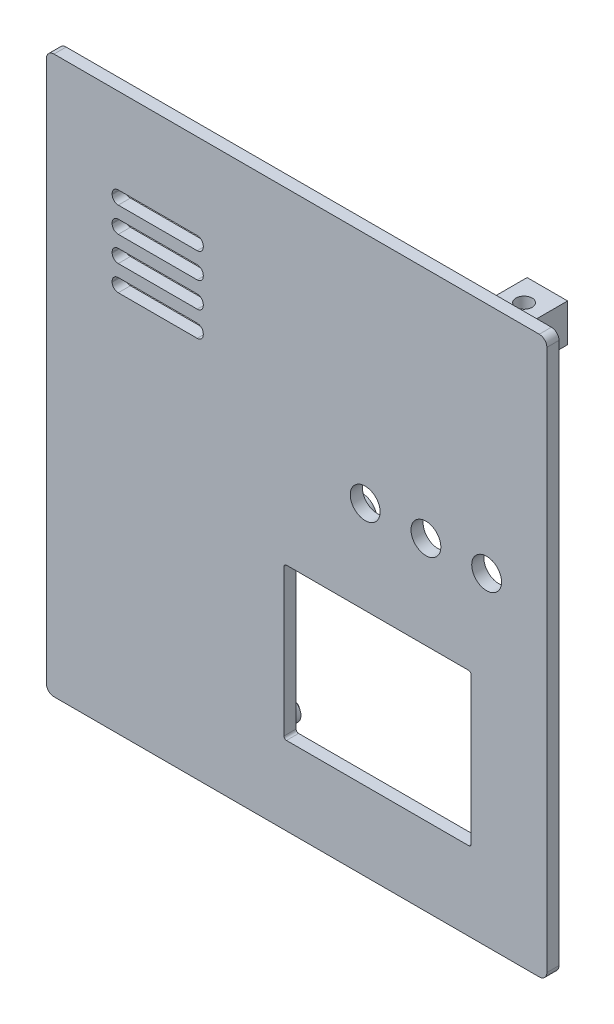
SolidWorks part; units mm, degrees
ref_plane "前视基准面" through (0, 0, 0) normal (0, 0, 1) x (1, 0, 0)
ref_plane "上视基准面" through (0, 0, 0) normal (0, 1, 0) x (1, 0, 0)
ref_plane "右视基准面" through (0, 0, 0) normal (1, 0, 0) x (0, 0, -1)
other "Configuration Table"
sketch "草图1" plane through (0, 0, 0) normal (0, 0, 1) x (1, 0, 0)
  line L0 (-2.5, -9.5) -> (93.4, -9.5)
  line L1 (94.9, -8) -> (94.9, 99)
  line L2 (93.4, 100.5) -> (-2.5, 100.5)
  line L3 (-4, 99) -> (-4, -8)
  arc A0 (93.4, -9.5) -> (94.9, -8) centre (93.4, -8) ccw
  arc A1 (94.9, 99) -> (93.4, 100.5) centre (93.4, 99) ccw
  arc A2 (-2.5, 100.5) -> (-4, 99) centre (-2.5, 99) ccw
  arc A3 (-4, -8) -> (-2.5, -9.5) centre (-2.5, -8) ccw
extrude "Lid_plate" add sketch "草图1" along normal blind 2.4 from offset 37.6
sketch "草图2" plane through (0, 0, 0) normal (0, 0, 1) x (1, 0, 0)
  line L0 (3, -7) -> (11, -7)
  line L1 (11, -7) -> (11, 0.5)
  line L2 (11, 0.5) -> (3, 0.5)
  line L3 (3, 0.5) -> (3, -7)
  line L4 (80, 90.5) -> (88, 90.5)
  line L5 (88, 90.5) -> (88, 98)
  line L6 (88, 98) -> (80, 98)
  line L7 (80, 98) -> (80, 90.5)
extrude "Two_side_fastening_tabs" add sketch "草图2" along normal blind 8.6 from offset 29
sketch "草图3" plane through (0, 0, 0) normal (0, 1, 0) x (1, 0, 0)
  circle A0 centre (7, -33.6) radius 1.6
extrude "M3_tab_bore_1" cut sketch "草图3" against normal blind 3.8 and the other way blind 3.8 from offset 3.25
sketch "草图4" plane through (0, 0, 0) normal (0, 1, 0) x (1, 0, 0)
  line L0 (9.875, -35.2599) -> (7, -36.9198)
  line L1 (7, -36.9198) -> (4.125, -35.2599)
  line L2 (4.125, -35.2599) -> (4.125, -31.9401)
  line L3 (4.125, -31.9401) -> (7, -30.2802)
  line L4 (7, -30.2802) -> (9.875, -31.9401)
  line L5 (9.875, -31.9401) -> (9.875, -35.2599)
extrude "M3_tab_captive_nut_1" cut sketch "草图4" against normal blind 1.3 and the other way blind 1.3 from offset 3.3
sketch "草图5" plane through (0, 0, 0) normal (0, 1, 0) x (1, 0, 0)
  line L0 (7, -30.25) -> (11.3, -30.25)
  line L1 (11.3, -30.25) -> (11.3, -36.95)
  line L2 (11.3, -36.95) -> (7, -36.95)
  line L3 (7, -36.95) -> (7, -30.25)
extrude "M3_tab_nut_loading_slot_1" cut sketch "草图5" against normal blind 1.3 and the other way blind 1.3 from offset 3.3
sketch "草图6" plane through (0, 0, 0) normal (0, 1, 0) x (1, 0, 0)
  circle A0 centre (84, -33.6) radius 1.6
extrude "M3_tab_bore_2" cut sketch "草图6" against normal blind 3.8 and the other way blind 3.8 from offset 94.25
sketch "草图7" plane through (0, 0, 0) normal (0, 1, 0) x (1, 0, 0)
  line L0 (86.875, -35.2599) -> (84, -36.9198)
  line L1 (84, -36.9198) -> (81.125, -35.2599)
  line L2 (81.125, -35.2599) -> (81.125, -31.9401)
  line L3 (81.125, -31.9401) -> (84, -30.2802)
  line L4 (84, -30.2802) -> (86.875, -31.9401)
  line L5 (86.875, -31.9401) -> (86.875, -35.2599)
extrude "M3_tab_captive_nut_2" cut sketch "草图7" against normal blind 1.3 and the other way blind 1.3 from offset 94.3
sketch "草图8" plane through (0, 0, 0) normal (0, 1, 0) x (1, 0, 0)
  line L0 (79.7, -30.25) -> (84, -30.25)
  line L1 (84, -30.25) -> (84, -36.95)
  line L2 (84, -36.95) -> (79.7, -36.95)
  line L3 (79.7, -36.95) -> (79.7, -30.25)
extrude "M3_tab_nut_loading_slot_2" cut sketch "草图8" against normal blind 1.3 and the other way blind 1.3 from offset 94.3
sketch "草图9" plane through (0, 0, 0) normal (0, 0, 1) x (1, 0, 0)
  line L0 (15, -6.8) -> (77, -6.8)
  line L1 (77, -6.8) -> (77, -5.6)
  line L2 (77, -5.6) -> (15, -5.6)
  line L3 (15, -5.6) -> (15, -6.8)
  line L4 (15, 96.6) -> (77, 96.6)
  line L5 (77, 96.6) -> (77, 97.8)
  line L6 (77, 97.8) -> (15, 97.8)
  line L7 (15, 97.8) -> (15, 96.6)
extrude "Side_locating_lips" add sketch "草图9" along normal blind 2 from offset 35.6
sketch "草图10" plane through (0, 0, 0) normal (0, 0, 1) x (1, 0, 0)
  line L0 (43.44, 6) -> (79.44, 6)
  line L1 (79.94, 6.5) -> (79.94, 35.5)
  line L2 (79.44, 36) -> (43.44, 36)
  line L3 (42.94, 35.5) -> (42.94, 6.5)
  arc A0 (79.44, 6) -> (79.94, 6.5) centre (79.44, 6.5) ccw
  arc A1 (79.94, 35.5) -> (79.44, 36) centre (79.44, 35.5) ccw
  arc A2 (43.44, 36) -> (42.94, 35.5) centre (43.44, 35.5) ccw
  arc A3 (42.94, 6.5) -> (43.44, 6) centre (43.44, 6.5) ccw
extrude "LCD_viewing_window" cut sketch "草图10" against normal through all and the other way through all
sketch "草图11" plane through (0, 0, 0) normal (0, 0, 1) x (1, 0, 0)
  circle A0 centre (38.5, 6) radius 2.1
  circle A1 centre (38.5, 36) radius 2.1
  circle A2 centre (89.5, 6) radius 2.1
  circle A3 centre (89.5, 36) radius 2.1
extrude "LCD_mounting_spacers" add sketch "草图11" along normal blind 3.3 from offset 34.3
sketch "草图12" plane through (0, 0, 0) normal (0, 0, 1) x (1, 0, 0)
  circle A0 centre (38.5, 6) radius 0.8
  circle A1 centre (89.5, 36) radius 0.8
extrude "Two_LCD_locating_pins" add sketch "草图12" along normal blind 1 from offset 33.3
sketch "草图13" plane through (0, 0, 0) normal (0, 0, 1) x (1, 0, 0)
  circle A0 centre (38.5, 36) radius 0.65
  circle A1 centre (89.5, 6) radius 0.65
extrude "Two_blind_M1p6_LCD_pilots" cut sketch "草图13" against normal blind 1.45 and the other way blind 1.45 from offset 35.75
sketch "草图14" plane through (0, 0, 0) normal (0, 0, 1) x (1, 0, 0)
  circle A0 centre (59, 54.355) radius 2.95
  circle A1 centre (71, 54.355) radius 2.95
  circle A2 centre (83, 54.355) radius 2.95
extrude "Three_button_guides" cut sketch "草图14" against normal through all and the other way through all
sketch "草图15" plane through (0, 0, 0) normal (0, 0, 1) x (1, 0, 0)
  circle A0 centre (54, 48.5) radius 2.9
  circle A1 centre (88, 60.2) radius 2.9
extrude "Button_retainer_bosses" add sketch "草图15" along normal blind 2 from offset 35.6
sketch "草图16" plane through (0, 0, 0) normal (0, 0, 1) x (1, 0, 0)
  circle A0 centre (54, 48.5) radius 1.1
  circle A1 centre (88, 60.2) radius 1.1
extrude "Button_retainer_pilot_holes" cut sketch "草图16" against normal blind 1.9 and the other way blind 1.9 from offset 37.5
sketch "草图17" plane through (0, 0, 0) normal (0, 0, 1) x (1, 0, 0)
  line L0 (10.2, 66) -> (25.8, 66)
  line L1 (27, 67.2) -> (27, 67.4)
  line L2 (25.8, 68.6) -> (10.2, 68.6)
  line L3 (9, 67.4) -> (9, 67.2)
  line L4 (10.2, 71) -> (25.8, 71)
  line L5 (27, 72.2) -> (27, 72.4)
  line L6 (25.8, 73.6) -> (10.2, 73.6)
  line L7 (9, 72.4) -> (9, 72.2)
  line L8 (10.2, 76) -> (25.8, 76)
  line L9 (27, 77.2) -> (27, 77.4)
  line L10 (25.8, 78.6) -> (10.2, 78.6)
  line L11 (9, 77.4) -> (9, 77.2)
  line L12 (10.2, 81) -> (25.8, 81)
  line L13 (27, 82.2) -> (27, 82.4)
  line L14 (25.8, 83.6) -> (10.2, 83.6)
  line L15 (9, 82.4) -> (9, 82.2)
  arc A0 (25.8, 66) -> (27, 67.2) centre (25.8, 67.2) ccw
  arc A1 (27, 67.4) -> (25.8, 68.6) centre (25.8, 67.4) ccw
  arc A2 (10.2, 68.6) -> (9, 67.4) centre (10.2, 67.4) ccw
  arc A3 (9, 67.2) -> (10.2, 66) centre (10.2, 67.2) ccw
  arc A4 (25.8, 71) -> (27, 72.2) centre (25.8, 72.2) ccw
  arc A5 (27, 72.4) -> (25.8, 73.6) centre (25.8, 72.4) ccw
  arc A6 (10.2, 73.6) -> (9, 72.4) centre (10.2, 72.4) ccw
  arc A7 (9, 72.2) -> (10.2, 71) centre (10.2, 72.2) ccw
  arc A8 (25.8, 76) -> (27, 77.2) centre (25.8, 77.2) ccw
  arc A9 (27, 77.4) -> (25.8, 78.6) centre (25.8, 77.4) ccw
  arc A10 (10.2, 78.6) -> (9, 77.4) centre (10.2, 77.4) ccw
  arc A11 (9, 77.2) -> (10.2, 76) centre (10.2, 77.2) ccw
  arc A12 (25.8, 81) -> (27, 82.2) centre (25.8, 82.2) ccw
  arc A13 (27, 82.4) -> (25.8, 83.6) centre (25.8, 82.4) ccw
  arc A14 (10.2, 83.6) -> (9, 82.4) centre (10.2, 82.4) ccw
  arc A15 (9, 82.2) -> (10.2, 81) centre (10.2, 82.2) ccw
extrude "Top_air_slots" cut sketch "草图17" against normal through all and the other way through all
